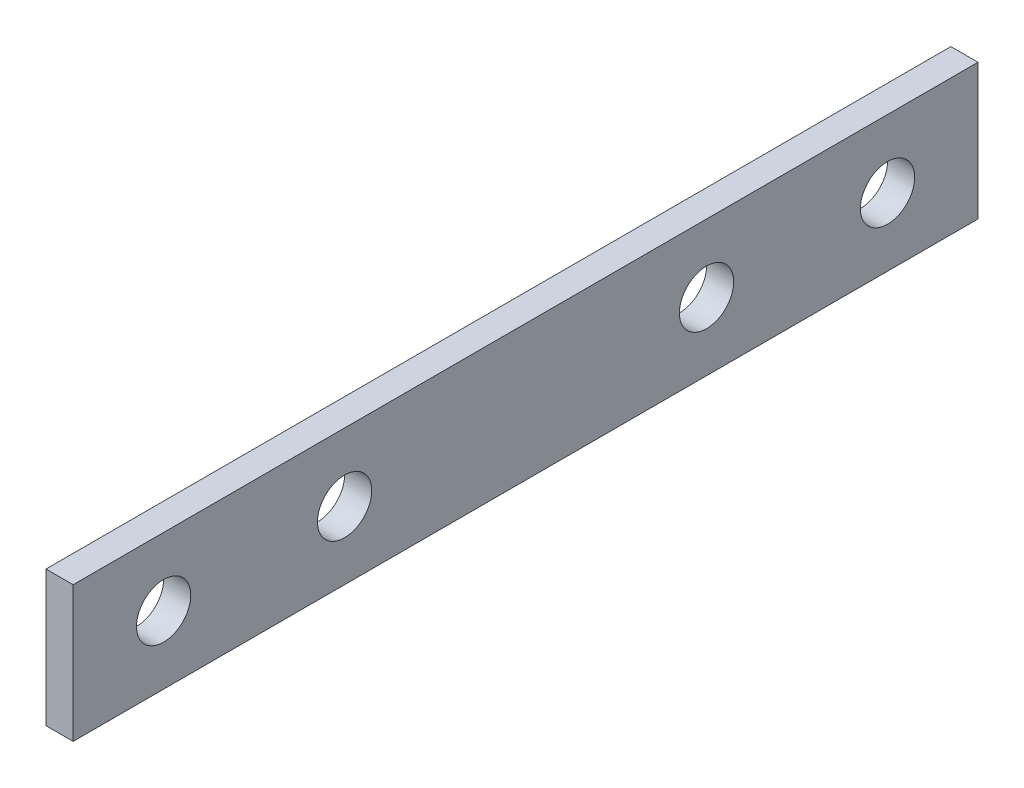
SolidWorks part; units mm, degrees
ref_plane "Спереди" through (0, 0, 0) normal (0, 0, 1) x (1, 0, 0)
ref_plane "Сверху" through (0, 0, 0) normal (0, 1, 0) x (1, 0, 0)
ref_plane "Справа" through (0, 0, 0) normal (1, 0, 0) x (0, 0, -1)
sketch "Эскиз1" plane through (0, 0, 0) normal (1, 0, 0) x (0, 0, -1)
  line L0 (-1000, 0) -> (49000, 0) construction
  line L1 (-50, -7.5) -> (50, -7.5)
  line L2 (-50, -7.5) -> (-50, 7.5)
  line L3 (-50, 7.5) -> (50, 7.5)
  line L4 (50, -7.5) -> (50, 7.5)
  line L5 (-50, -7.5) -> (50, 7.5) construction
  line L6 (-50, 7.5) -> (50, -7.5) construction
  line L7 (0, -1000) -> (0, 49000) construction
  circle A0 centre (-40, 0) radius 3
  circle A1 centre (-20, 0) radius 3
  circle A2 centre (20, 0) radius 3
  circle A3 centre (40, 0) radius 3
  point P0 (0, 0)
  dimension "D3" = 6
  dimension "D1" = 15
  dimension "D2" = 100
  dimension "D4" = 20
  dimension "D5" = 10
extrude "Бобышка-Вытянуть1" add sketch "Эскиз1" along normal blind 3
